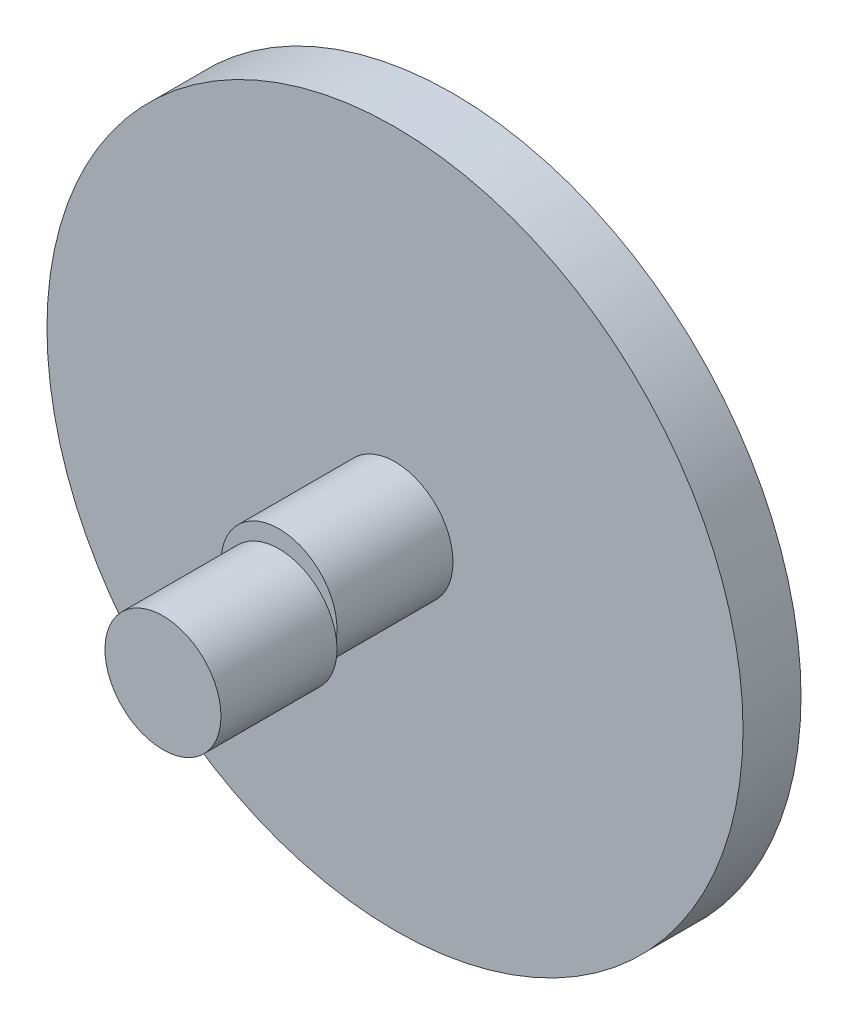
SolidWorks part; units mm, degrees
ref_plane "Front Plane" through (0, 0, 0) normal (0, 0, 1) x (1, 0, 0)
ref_plane "Top Plane" through (0, 0, 0) normal (0, 1, 0) x (1, 0, 0)
ref_plane "Right Plane" through (0, 0, 0) normal (1, 0, 0) x (0, 0, -1)
sketch "Sketch1" plane through (0, 0, 0) normal (0, 0, 1) x (1, 0, 0)
  line L0 (0, 0) -> (-25.4, 0) construction
  circle A0 centre (0, 0) radius 38.1
  point P18 (0, 0)
  dimension "D4" = 76.2
extrude "Boss-Extrude1" add sketch "Sketch1" along normal blind 6.35
sketch "Sketch2" plane through (0, 0, 6.35) normal (0, 0, 1) x (1, 0, 0)
  circle A0 centre (0, 0) radius 6.35
  circle A1 centre (0, 0) radius 38.1 construction
  point P5 (0, -1.905)
  point P7 (0, 0)
  point P9 (-5.2124, -1.905)
  dimension "D1" = 12.7
  dimension "D2" = 0
  dimension "D3" = 0
extrude "Boss-Extrude2" add sketch "Sketch2" along normal blind 12.7
sketch "Sketch3" plane through (0, 0, 19.05) normal (0, 0, 1) x (1, 0, 0)
  circle A0 centre (0, -1.905) radius 6.35
  point P2 (0, -1.905)
  point P4 (0, 0)
  point P8 (-46.4128, 16.9831)
  dimension "D1" = 12.7
  dimension "D2" = 0
  dimension "D3" = 1.905
extrude "Boss-Extrude3" add sketch "Sketch3" along normal blind 12.7
sketch "Sketch4" plane through (0, 0, 0) normal (0, 0, -1) x (-1, 0, 0)
  circle A0 centre (0, 0) radius 25.4 construction
  circle A1 centre (-25.4, 0) radius 3.175
  circle A2 centre (-12.7, 21.997) radius 3.175
  circle A3 centre (12.7, 21.997) radius 3.175
  circle A4 centre (25.4, 0) radius 3.175
  circle A5 centre (12.7, -21.997) radius 3.175
  circle A6 centre (-12.7, -21.997) radius 3.175
  circle A7 centre (0, 0) radius 38.1 construction
  point P17 (0, 0)
  dimension "D1" = 50.8
  dimension "D2" = 6.35
  dimension "D3" = 6
extrude "Cut-Extrude1" cut sketch "Sketch4" against normal blind 3.175
